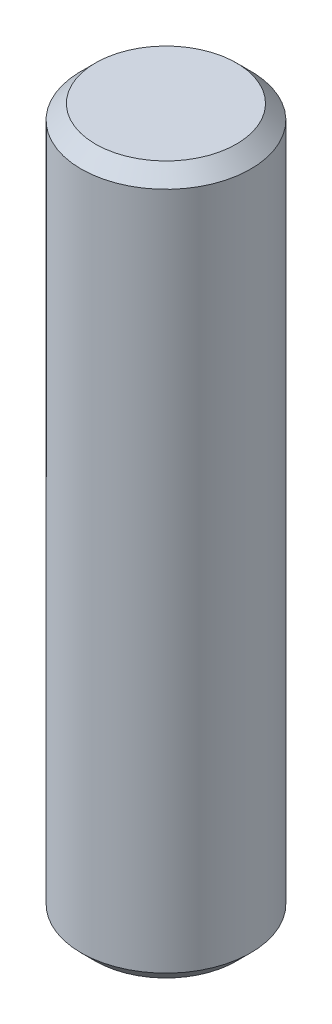
SolidWorks part; units mm, degrees
ref_plane "Front Plane" through (0, 0, 0) normal (0, 0, 1) x (1, 0, 0)
ref_plane "Top Plane" through (0, 0, 0) normal (0, 1, 0) x (1, 0, 0)
ref_plane "Right Plane" through (0, 0, 0) normal (1, 0, 0) x (0, 0, -1)
ref_plane "Plane1" through (0, 0, 0) normal (0, 0, -1) x (-1, 0, 0)
sketch "Sketch1" plane through (0, 0, 0) normal (0, 0, -1) x (-1, 0, 0)
  line L0 (-2.4882, 0) -> (0, 0)
  line L1 (0, 0) -> (0, 25)
  line L2 (0, 25) -> (-2.4882, 25)
  line L3 (-2.4882, 25) -> (-2.9962, 24.492)
  line L4 (-2.9962, 24.492) -> (-2.9962, 0.508)
  line L5 (-2.9962, 0.508) -> (-2.4882, 0)
  line L6 (0, 0) -> (0, 25) construction
revolve "Revolve1" add sketch "Sketch1" angle 360 about L6
